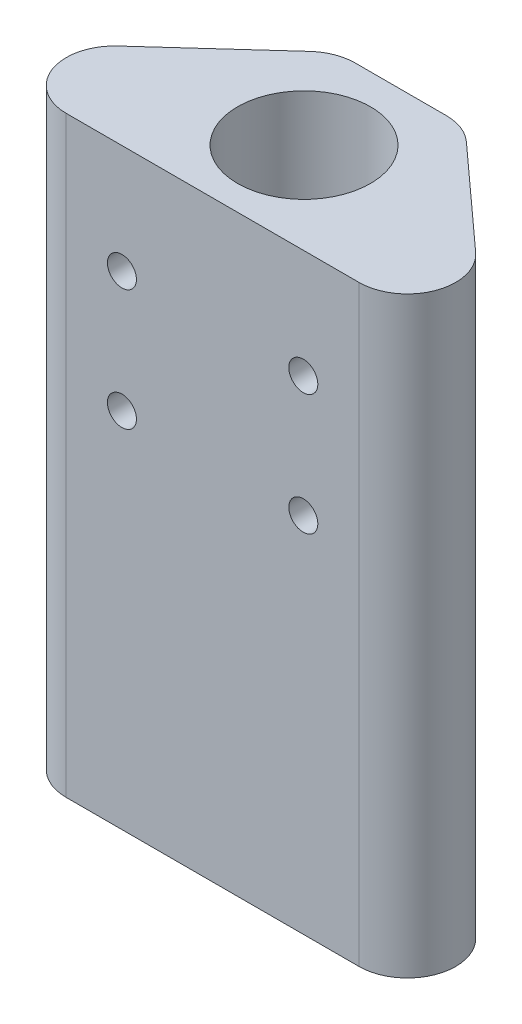
SolidWorks part; units mm, degrees
ref_plane "Front Plane" through (0, 0, 0) normal (0, 0, 1) x (1, 0, 0)
ref_plane "Top Plane" through (0, 0, 0) normal (0, 1, 0) x (1, 0, 0)
ref_plane "Right Plane" through (0, 0, 0) normal (1, 0, 0) x (0, 0, -1)
sketch "Sketch1" plane through (0, 0, 0) normal (0, 1, 0) x (1, 0, 0)
  line L0 (0, 0) -> (0, -3.25) construction
  line L1 (-5.3208, 8) -> (-22.469, -7.56)
  line L3 (-17.719, 0) -> (17.719, 0) construction
  line L4 (5.3208, 8) -> (22.469, -7.56)
  line L5 (-22.469, -7.56) -> (22.469, -7.56)
  line L6 (-5.3208, 8) -> (5.3208, 8)
  circle A0 centre (0, 0) radius 3.25
  dimension "D1" = 6.5
  dimension "D2" = 42.22
  dimension "D3" = 7.56
  dimension "D4" = 9.5
  dimension "D5" = 8
extrude "Boss-Extrude1" add sketch "Sketch1" along normal blind 49
fillet "Fillet1" radius 4 4 edges at (22.469, 24.5, 7.56) (-22.469, 24.5, 7.56) (5.3208, 24.5, -8) (-5.3208, 24.5, -8)
sketch "Sketch2" plane through (0, 49, 0) normal (0, 1, 0) x (1, 0, 0)
  circle A0 centre (0, 0) radius 5.5
  dimension "D1" = 11
extrude "Cut-Extrude1" cut sketch "Sketch2" along direction (0, -1, 0) on the side against the normal offset from surface (33 mm away) 16
sketch "Sketch3" plane through (0, 0, 7.56) normal (0, 0, 1) x (1, 0, 0)
  line L0 (-12.1082, 0) -> (12.1082, 0) construction
  line L1 (7.5, 30) -> (-7.5, 30) construction
  line L2 (7.5, 30) -> (7.5, 40) construction
  line L3 (7.5, 40) -> (-7.5, 40) construction
  line L4 (-7.5, 30) -> (-7.5, 40) construction
  line L5 (7.5, 30) -> (-7.5, 40) construction
  line L6 (7.5, 40) -> (-7.5, 30) construction
  circle A0 centre (-7.5, 40) radius 1.2
  circle A1 centre (7.5, 40) radius 1.2
  circle A2 centre (7.5, 30) radius 1.2
  circle A3 centre (-7.5, 30) radius 1.2
  point P0 (0, 35)
  dimension "D4" = 2.4
  dimension "D1" = 15
  dimension "D2" = 10
  dimension "D3" = 35
extrude "Cut-Extrude2" cut sketch "Sketch3" against normal through all
